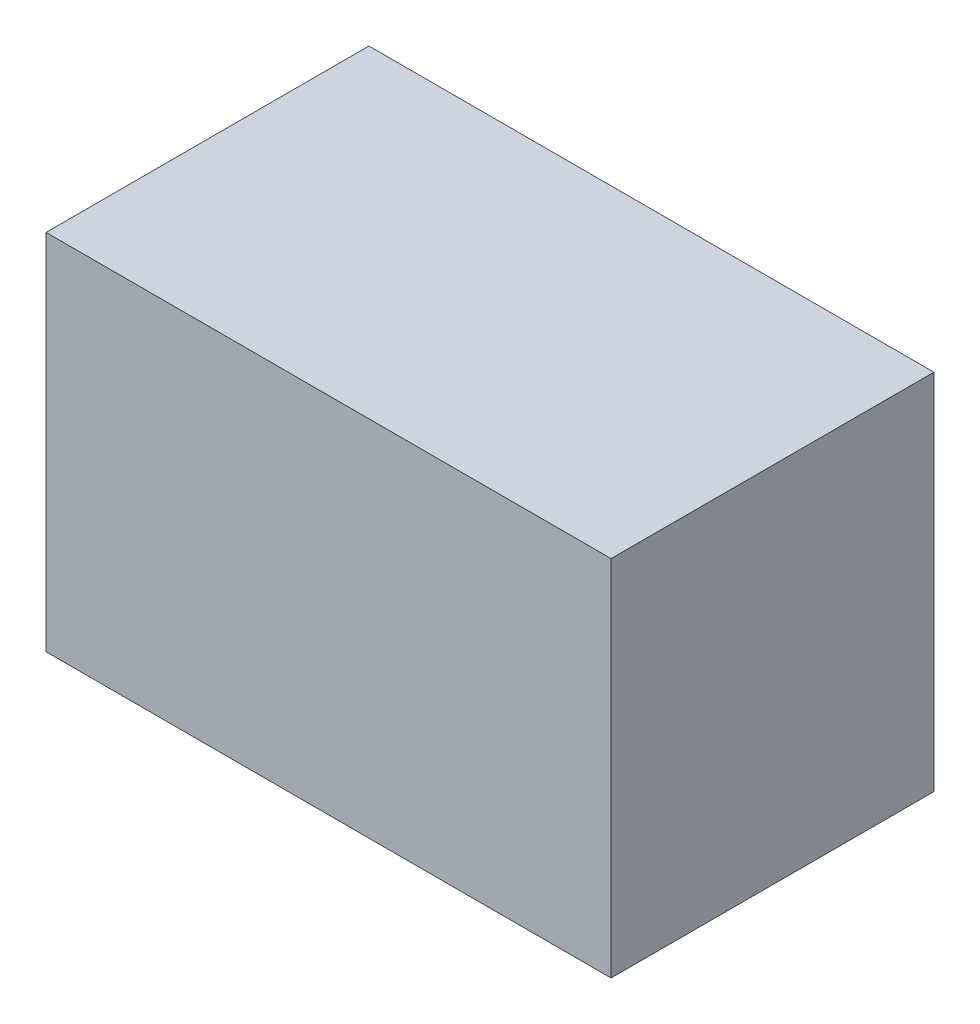
SolidWorks part; units mm, degrees
ref_plane "前视基准面" through (0, 0, 0) normal (0, 0, 1) x (1, 0, 0)
ref_plane "上视基准面" through (0, 0, 0) normal (0, 1, 0) x (1, 0, 0)
ref_plane "右视基准面" through (0, 0, 0) normal (1, 0, 0) x (0, 0, -1)
sketch "草图1" plane through (0, 0, 0) normal (0, 0, 1) x (1, 0, 0)
  line L1 (-59.5126, 4.399) -> (10.4874, 4.399)
  line L2 (-59.5126, 4.399) -> (-59.5126, -40.601)
  line L3 (-59.5126, -40.601) -> (10.4874, -40.601)
  line L4 (10.4874, 4.399) -> (10.4874, -40.601)
  dimension "D1" = 70
  dimension "D2" = 45
extrude "凸台-拉伸1" add sketch "草图1" along normal blind 40
